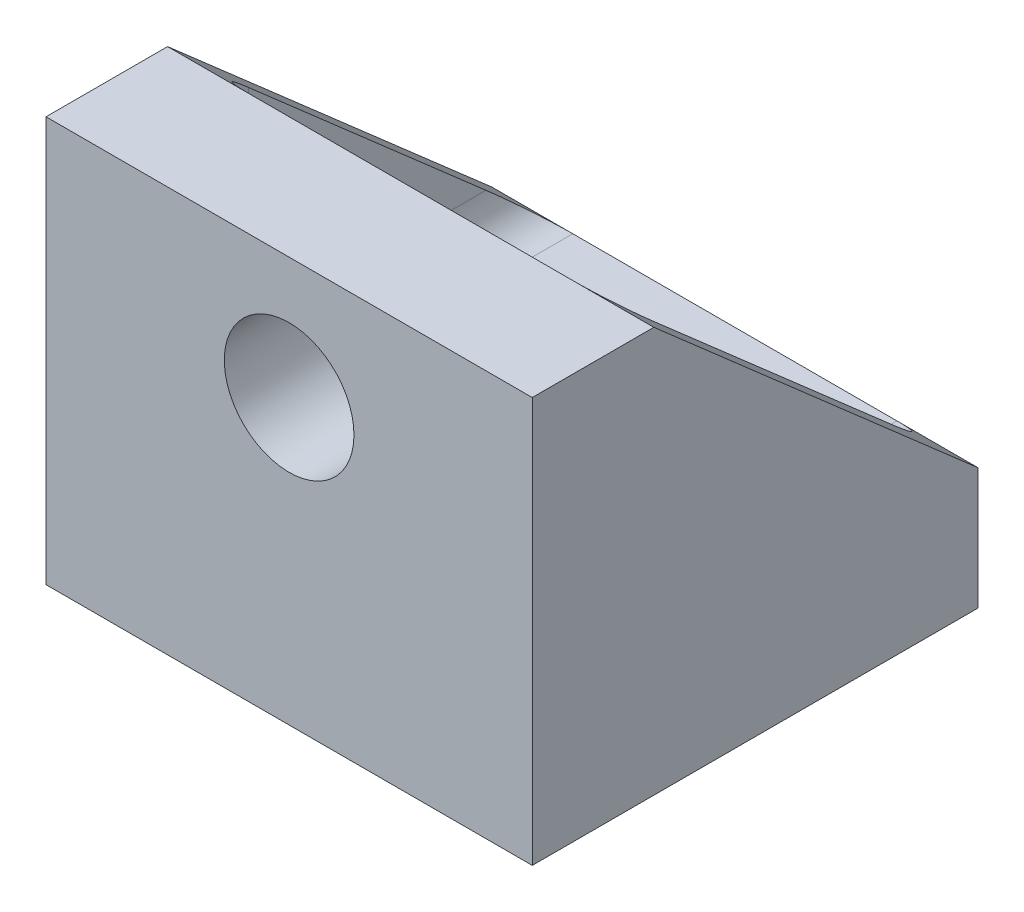
SolidWorks part; units mm, degrees
ref_plane "Front Plane" through (0, 0, 0) normal (0, 0, 1) x (1, 0, 0)
ref_plane "Top Plane" through (0, 0, 0) normal (0, 1, 0) x (1, 0, 0)
ref_plane "Right Plane" through (0, 0, 0) normal (1, 0, 0) x (0, 0, -1)
sketch "Sketch2" plane through (0, 0, 0) normal (0, 1, 0) x (1, 0, 0)
  line L1 (-5, 4) -> (5, 4)
  line L2 (-5, 4) -> (-5, -4)
  line L3 (-5, -4) -> (5, -4)
  line L4 (5, 4) -> (5, -4)
  line L5 (-5, 4) -> (5, -4) construction
  line L6 (-5, -4) -> (5, 4) construction
  circle A1 centre (0, 0.5) radius 1.6
  point P0 (0, 0)
  point P8 (0, 0)
  dimension "D2" = 10
  dimension "D3" = 3.2
  dimension "D1" = 8
  dimension "D4" = 5
  dimension "D5" = 3.5
extrude "Boss-Extrude1" add sketch "Sketch2" along normal blind 3
sketch "Sketch3" plane through (0, 0, 4) normal (0, 0, 1) x (1, 0, 0)
  line L1 (-5, 0) -> (5, 0)
  line L2 (-5, 0) -> (-5, 10)
  line L3 (-5, 10) -> (5, 10)
  line L4 (5, 0) -> (5, 10)
  circle A0 centre (0, 7) radius 1.6
  dimension "D4" = 3.2
  dimension "D1" = 10
  dimension "D2" = 10
  dimension "D3" = 7
extrude "Boss-Extrude2" add sketch "Sketch3" along normal blind 3 contours A0 | L2 L3 L4 L1
sketch "Sketch4" plane through (-5, 0, 0) normal (-1, 0, 0) x (0, 0, 1)
  line L0 (-4, 3) -> (4, 10)
  line L1 (-4, 0) -> (7, 0)
  line L2 (-4, 0) -> (-4, 3)
  line L3 (4, 10) -> (7, 10)
  line L4 (7, 0) -> (7, 10)
extrude "Boss-Extrude3" add sketch "Sketch4" along normal blind 1
mirror "Mirror1" about plane through (0, 0, 0) normal (1, 0, 0) of "Boss-Extrude3"
fillet "Fillet1" radius 1 1 edges at (0, 3, 4)
fillet "Fillet2" radius 1 6 edges at (5, 7, 4) (5, 3.2929, 3.7071) (-5, 3, -0.5) (-5, 3.2929, 3.7071) (5, 3, -0.5) (-5, 7, 4)
equation "\"Hole Size\"= 3.2mm"
equation "\"D4@Sketch3\"=\"Hole Size\""
equation "\"D3@Sketch2\"=\"Hole Size\""
